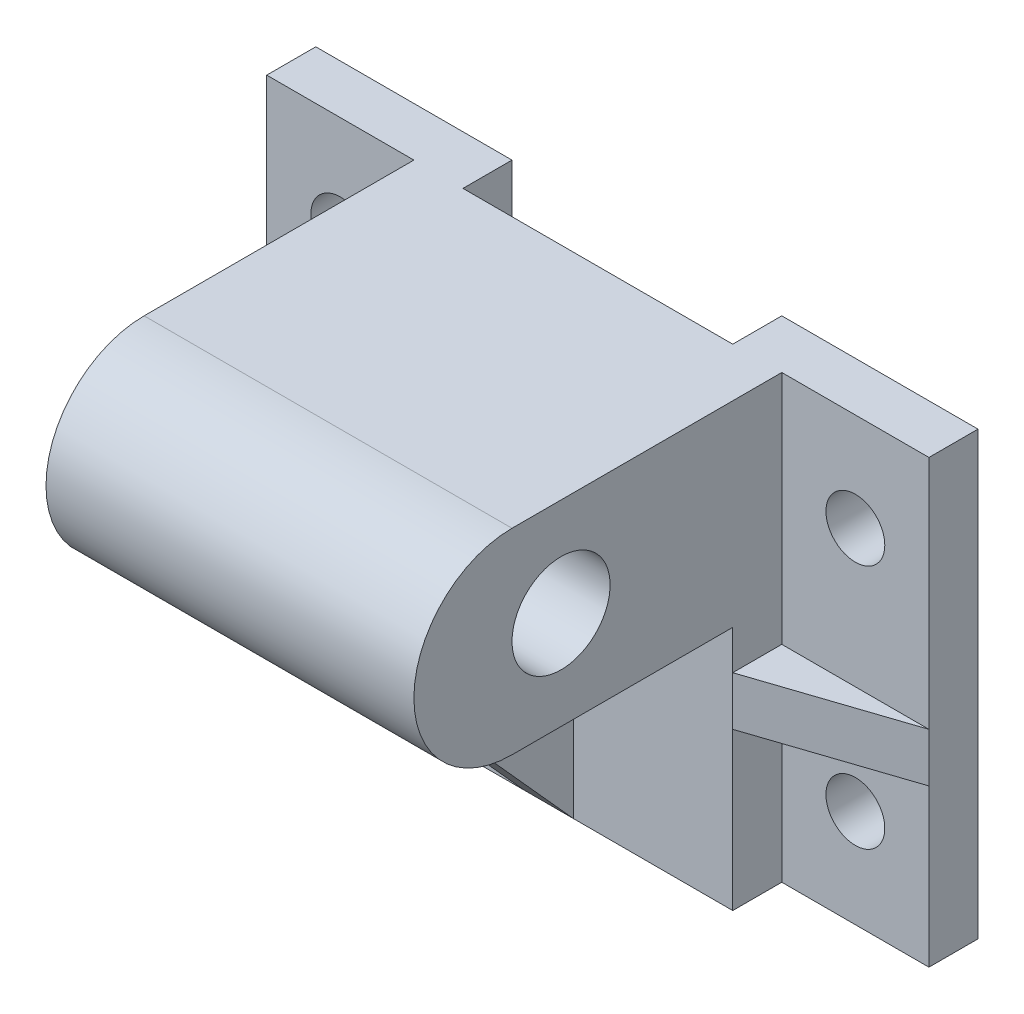
SolidWorks part; units mm, degrees
ref_plane "Front Plane" through (0, 0, 0) normal (0, 0, 1) x (1, 0, 0)
ref_plane "Top Plane" through (0, 0, 0) normal (0, 1, 0) x (1, 0, 0)
ref_plane "Right Plane" through (0, 0, 0) normal (1, 0, 0) x (0, 0, -1)
sketch "Sketch1" plane through (0, 0, 0) normal (0, 0, 1) x (1, 0, 0)
  line L1 (-37.5, -45) -> (37.5, -45)
  line L2 (-37.5, -45) -> (-37.5, 45)
  line L3 (-37.5, 45) -> (37.5, 45)
  line L4 (37.5, -45) -> (37.5, 45)
  line L5 (-37.5, -45) -> (37.5, 45) construction
  line L6 (-37.5, 45) -> (37.5, -45) construction
  point P0 (0, 0)
  dimension "D1" = 90
  dimension "D2" = 75
extrude "Boss-Extrude1" add sketch "Sketch1" along normal blind 10
sketch "Sketch2" plane through (0, 0, 10) normal (0, 0, 1) x (1, 0, 0)
  line L0 (37.5, -45) -> (37.5, 45) construction
  line L1 (-37.5, 45) -> (37.5, 45)
  line L2 (-37.5, 45) -> (-37.5, 5)
  line L3 (-37.5, 5) -> (37.5, 5)
  line L4 (37.5, 45) -> (37.5, 5)
  dimension "D1" = 40
extrude "Boss-Extrude2" add sketch "Sketch2" along normal blind 45
sketch "Sketch5" plane through (0, 0, 0) normal (0, 0, -1) x (-1, 0, 0)
  line L0 (37.5, -45) -> (-37.5, -45) construction
  line L1 (-37.5, 45) -> (-27.5, 45)
  line L2 (-37.5, 45) -> (-37.5, -45)
  line L3 (-37.5, -45) -> (-27.5, -45)
  line L4 (-27.5, 45) -> (-27.5, -45)
  line L6 (37.5, 45) -> (27.5, 45)
  line L7 (37.5, 45) -> (37.5, -45)
  line L8 (37.5, -45) -> (27.5, -45)
  line L9 (27.5, 45) -> (27.5, -45)
  dimension "D1" = 10
  dimension "D2" = 10
extrude "Boss-Extrude3" add sketch "Sketch5" along normal blind 10
sketch "Sketch7" plane through (37.5, 0, 0) normal (1, 0, 0) x (0, 0, -1)
  line L0 (-55, 45) -> (10, 45) construction
  line L1 (10, -45) -> (0, -45)
  line L2 (10, -45) -> (10, 45)
  line L3 (10, 45) -> (0, 45)
  line L4 (0, -45) -> (0, 45)
  dimension "D1" = 10
extrude "Boss-Extrude4" add sketch "Sketch7" along normal blind 30
ref_plane "Plane1" through (0, 0, 0) normal (1, 0, 0) x (0, 0, -1)
mirror "Mirror1" about plane through (0, 0, 0) normal (1, 0, 0) of "Boss-Extrude4", "Boss-Extrude3"
ref_plane "Plane2" through (-37.5, 0, 0) normal (-1, 0, 0) x (0, 0, 1)
sketch "Sketch14" plane through (-37.5, 0, 0) normal (-1, 0, 0) x (0, 0, 1)
  line L0 (55, 45) -> (55, 5) construction
  circle A0 centre (55, 25) radius 20
extrude "Boss-Extrude6" add sketch "Sketch14" against normal blind 75
sketch "Sketch15" plane through (-37.5, 0, 0) normal (-1, 0, 0) x (0, 0, 1)
  line L0 (0, 45) -> (0, -45) construction
  line L1 (55, 5) -> (10, 5) construction
  circle A0 centre (45, 25) radius 10
  point P6 (47.5541, 6.6445)
  point P9 (47.5618, 14.7528)
  dimension "D3" = 20
  dimension "D1" = 45
  dimension "D2" = 20
extrude "Cut-Extrude3" cut sketch "Sketch15" against normal blind 75 contours A0
sketch "Sketch16" plane through (0, 0, 0) normal (0, 0, 1) x (1, 0, 0)
  line L0 (-67.5, 45) -> (-67.5, -45) construction
  line L1 (-67.5, 45) -> (-37.5, 45) construction
  line L2 (67.5, 45) -> (67.5, -45) construction
  line L3 (67.5, 45) -> (37.5, 45) construction
  circle A0 centre (-52.5, 25) radius 6
  circle A1 centre (52.5, 25) radius 6
  circle A2 centre (52.5, -25) radius 6
  circle A3 centre (-52.5, -25) radius 6
  dimension "D1" = 15
  dimension "D3" = 15
  dimension "D2" = 20
  dimension "D4" = 20
extrude "Cut-Extrude4" cut sketch "Sketch16" against normal blind 75
ref_plane "Plane6" through (0, -8, 0) normal (0, -1, 0) x (-1, 0, 0)
ref_plane "Plane7" through (0, 0, 0) normal (-1, 0, 0) x (0, 0, 1)
sketch "Sketch24" plane through (0, 0, 0) normal (-1, 0, 0) x (0, 0, 1)
  line L0 (10, -45) -> (55, 5)
rib "Rib16" sketch "Sketch24" sketch "Sketch24" thickness 10 extrusion direction parallel to sketch draft on no parameters "D1"=10
sketch "Sketch25" plane through (0, -8, 0) normal (0, -1, 0) x (-1, 0, 0)
  line L0 (-67.5, 0) -> (-37.5, -10)
rib "Rib17" sketch "Sketch25" sketch "Sketch25" thickness 10 extrusion direction parallel to sketch draft on no parameters "D1"=10
sketch "Sketch26" plane through (0, -8, 0) normal (0, -1, 0) x (-1, 0, 0)
  line L0 (67.5, 0) -> (37.5, -10)
rib "Rib18" sketch "Sketch26" sketch "Sketch26" thickness 10 extrusion direction parallel to sketch draft on no parameters "D1"=10
